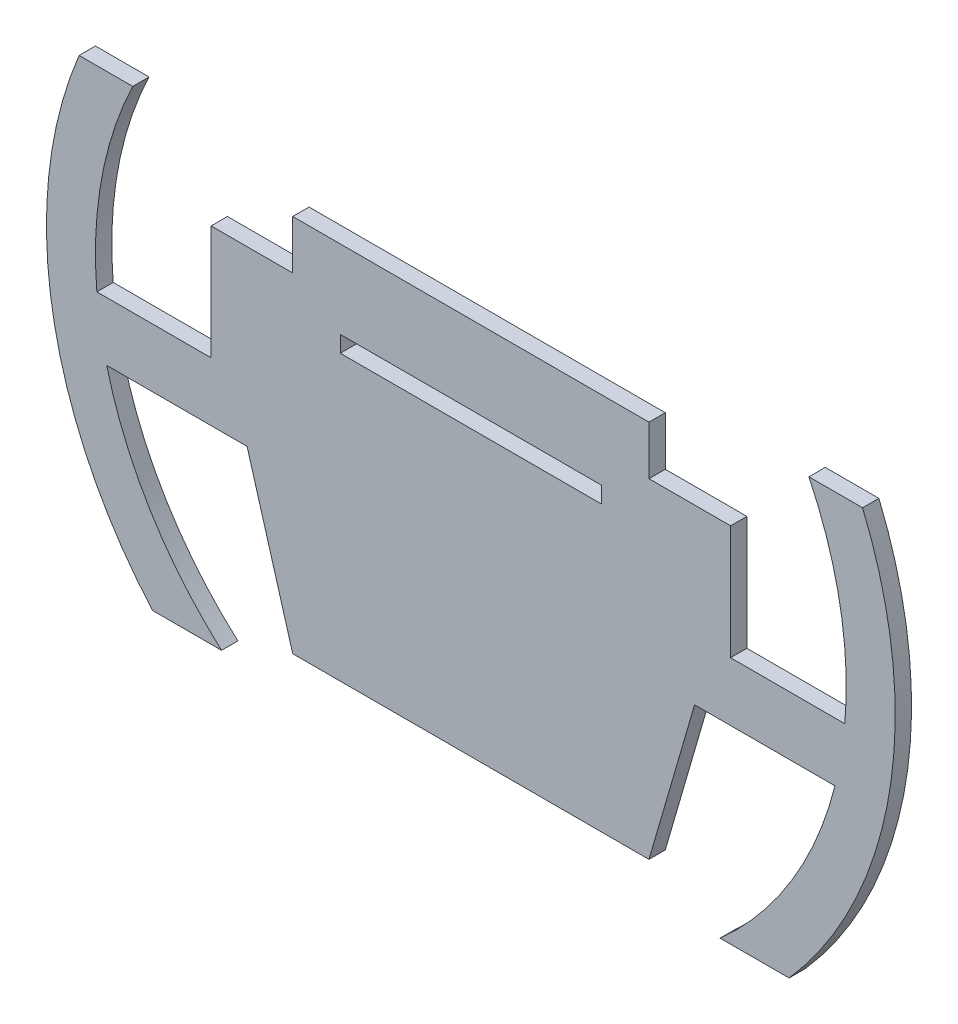
SolidWorks part; units mm, degrees
material "1.6566 (17NiCrMo6-4)"
ref_plane "Plan de face" through (0, 0, 0) normal (0, 0, 1) x (1, 0, 0)
ref_plane "Plan de dessus" through (0, 0, 0) normal (0, 1, 0) x (1, 0, 0)
ref_plane "Plan de droite" through (0, 0, 0) normal (1, 0, 0) x (0, 0, -1)
sketch "Esquisse1" plane through (0, 0, 0) normal (0, 0, 1) x (1, 0, 0)
  line L0 (0, 0) -> (296.2293, 0) construction
  line L1 (0, 0) -> (0, 97.4663) construction
  line L2 (-114.5644, -10) -> (-89.5644, -10)
  line L3 (-89.5644, -10) -> (-89.5644, 25)
  line L4 (-89.5644, 25) -> (-54.5644, 25)
  line L5 (-54.5644, 25) -> (-54.5644, 40)
  line L6 (-54.5644, 40) -> (54.5644, 40)
  line L7 (114.5644, -10) -> (89.5644, -10)
  line L8 (89.5644, -10) -> (89.5644, 25)
  line L9 (89.5644, 25) -> (54.5644, 25)
  line L10 (54.5644, 25) -> (54.5644, 40)
  line L11 (0, -18) -> (-148.6579, -18) construction
  line L12 (-111.5392, -28) -> (-68.5392, -28)
  line L13 (111.5392, -28) -> (68.5392, -28)
  line L14 (-68.5392, -28) -> (-54.5644, -76)
  line L15 (68.5392, -28) -> (54.5644, -76)
  line L16 (103.5616, 50) -> (120, 50)
  line L17 (76.3479, -86) -> (97.4885, -86)
  line L18 (-54.5644, -76) -> (54.5644, -76)
  line L20 (-103.5616, 50) -> (-120, 50)
  line L21 (-103.5616, 50) -> (-120, 50)
  line L22 (-76.3479, -86) -> (-97.4885, -86)
  arc A1 (120, 50) -> (97.4885, -86) centre (0, 0) cw
  arc A4 (111.5392, -28) -> (76.3479, -86) centre (0, 0) cw
  arc A5 (103.5616, 50) -> (114.5644, -10) centre (0, 0) cw
  arc A6 (-103.5616, 50) -> (-114.5644, -10) centre (0, 0) ccw
  arc A7 (-120, 50) -> (-97.4885, -86) centre (0, 0) ccw
  arc A8 (-111.5392, -28) -> (-76.3479, -86) centre (0, 0) ccw
  point P21 (0, 40)
  point P31 (0, -76)
  dimension "D2" = 114.5644
  dimension "D11" = 115
  dimension "D14" = 130
  dimension "D3" = 10
  dimension "D4" = 35
  dimension "D5" = 15
  dimension "D6" = 25
  dimension "D7" = 35
  dimension "D8" = 18
  dimension "D9" = 43
  dimension "D10" = 10
  dimension "D12" = 10
  dimension "D13" = 10
extrude "Boss.-Extru.1" add sketch "Esquisse1" along normal blind 5 contours A8 L12 L14 L18 L15 L13 A4 L17 A1 L16 A5 L7 L8 L9 L10 L6 L5 L4 L3 L2 A6 L20 A7 L22
sketch "Esquisse3" plane through (0, 0, 5) normal (0, 0, 1) x (1, 0, 0)
  line L0 (0, 0) -> (156.6081, 0) construction
  line L1 (0, 0) -> (0, 64.5981) construction
  line L2 (79.5644, 25) -> (54.5644, 25)
  line L3 (89.5644, 15) -> (89.5644, -8.1942)
  line L4 (54.5644, 25) -> (54.5644, -8.1942)
  line L5 (89.5644, -8.1942) -> (54.5644, -8.1942)
  line L6 (79.5644, 25) -> (89.9272, 25)
  line L7 (89.9272, 25) -> (89.9272, 15)
  line L8 (89.9272, 15) -> (89.5644, 15)
  arc A0 (89.5644, 15) -> (79.5644, 25) centre (79.5644, 15) ccw
  point P14 (89.5644, 25)
  line M20 (89.5644, -10) -> (89.5644, 25)
  line M21 (89.5644, 25) -> (54.5644, 25)
  dimension "D1" = 10
extrude "Enlèv. mat.-Extru.1" cut sketch "Esquisse3" against normal through all contours A0 M20 M21
sketch "Esquisse6" plane through (0, 0, 5) normal (0, 0, 1) x (1, 0, 0)
  line L0 (-79.5644, 25) -> (-69.3606, 25)
  line L1 (-89.5644, 15) -> (-89.5644, 6.2969)
  line L2 (-69.3606, 25) -> (-69.3606, 6.2969)
  line L3 (-89.5644, 6.2969) -> (-69.3606, 6.2969)
  line L4 (-89.5644, 25) -> (-54.5644, 25) construction
  line L5 (-89.5644, 25) -> (-73.2791, 25)
  line L6 (-89.5644, 25) -> (-89.5644, 13.0143)
  arc A0 (-89.5644, 15) -> (-79.5644, 25) centre (-79.5644, 15) cw
  point P9 (-89.5644, 25)
  line M7 (-54.5644, 25) -> (-89.5644, 25)
  line M8 (-89.5644, 25) -> (-89.5644, -10)
  dimension "D1" = 10
extrude "Enlèv. mat.-Extru.2" cut sketch "Esquisse6" against normal through all contours A0 M8 M7
sketch "Esquisse7" plane through (0, 0, 5) normal (0, 0, 1) x (1, 0, 0)
  line L0 (-89.5644, -10) -> (-79.5644, -10)
  line L1 (-79.5644, -10) -> (-79.5644, 32.45)
  line L2 (-79.5644, 32.45) -> (-89.5644, 32.45)
  line L3 (-89.5644, 32.45) -> (-89.5644, -10)
  line L4 (0, 0) -> (0, 63.7685) construction
  line L5 (0, 0) -> (80.4357, 0) construction
  line L6 (-32.1174, -18) -> (33.2543, -18) construction
  line L7 (79.5644, 32.45) -> (89.5644, 32.45)
  line L8 (89.5644, 32.45) -> (89.5644, -10)
  line L9 (89.5644, -10) -> (79.5644, -10)
  line L10 (79.5644, -10) -> (79.5644, 32.45)
  dimension "D1" = 10
  dimension "D2" = 18
extrude "Enlèv. mat.-Extru.5" cut sketch "Esquisse7" against normal through all
sketch "Esquisse8" plane through (0, 0, 5) normal (0, 0, 1) x (1, 0, 0)
  line L0 (0, 0) -> (0, 67.6939) construction
  line L2 (-40, 16) -> (40, 16)
  line L3 (-40, 16) -> (-40, 11)
  line L4 (-40, 11) -> (40, 11)
  line L5 (40, 16) -> (40, 11)
  line L6 (-40, 16) -> (40, 11) construction
  line L7 (-40, 11) -> (40, 16) construction
  point P1 (0, 13.5)
  dimension "D1" = 80
  dimension "D2" = 5
  dimension "D3" = 13.5
extrude "Enlèv. mat.-Extru.8" cut sketch "Esquisse8" against normal blind 5
